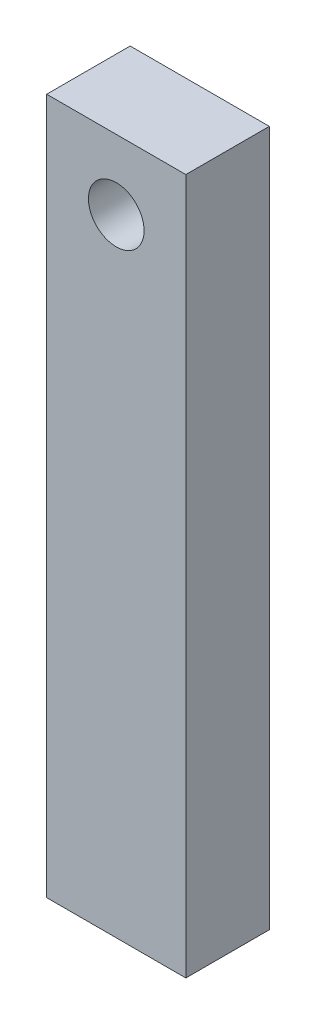
SolidWorks part; units mm, degrees
ref_plane "Plano frontal" through (0, 0, 0) normal (0, 0, 1) x (1, 0, 0)
ref_plane "Plano superior" through (0, 0, 0) normal (0, 1, 0) x (1, 0, 0)
ref_plane "Plano direito" through (0, 0, 0) normal (1, 0, 0) x (0, 0, -1)
sketch "Esboço1" plane through (0, 0, 0) normal (0, 0, 1) x (1, 0, 0)
  line L1 (4.4932, 0) -> (-5.5068, 0)
  line L2 (4.4932, 0) -> (4.4932, 50)
  line L3 (4.4932, 50) -> (-5.5068, 50)
  line L4 (-5.5068, 0) -> (-5.5068, 50)
  dimension "D1" = 10
  dimension "D2" = 50
extrude "Ressalto-extrusão1" add sketch "Esboço1" along normal blind 6
sketch "Esboço2" plane through (0, 0, 6) normal (0, 0, 1) x (1, 0, 0)
  line L0 (4.4932, 0) -> (4.4932, 50) construction
  line L1 (4.4932, 50) -> (-5.5068, 50) construction
  circle A0 centre (-0.5068, 45) radius 2
  dimension "D1" = 4
  dimension "D2" = 5
  dimension "D3" = 5
extrude "Corte-extrusão1" cut sketch "Esboço2" against normal through all
